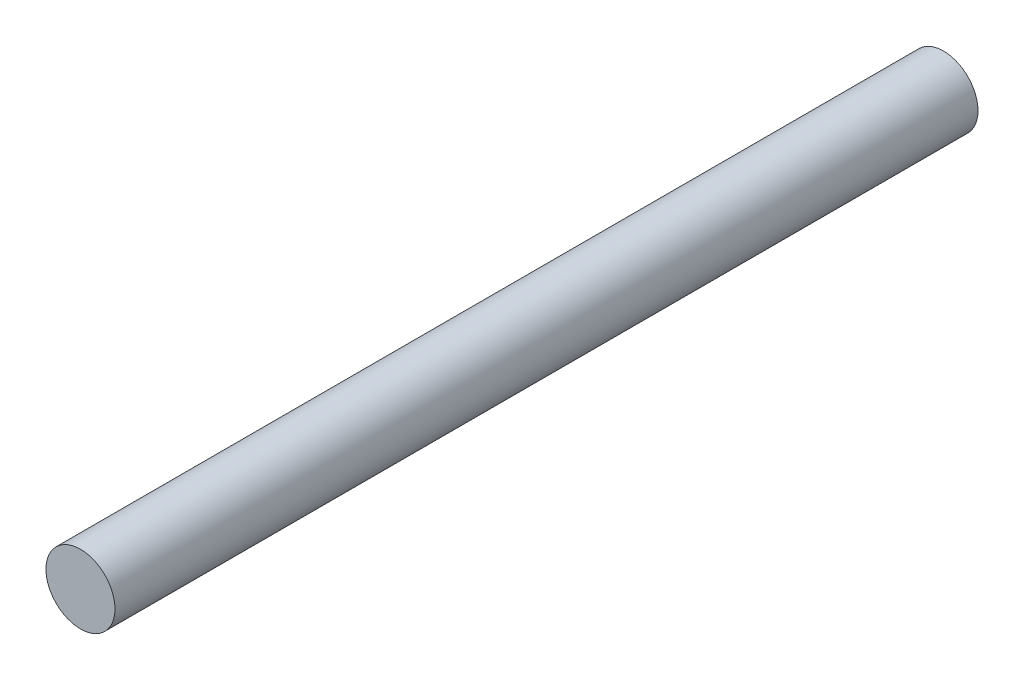
SolidWorks part; units mm, degrees
ref_plane "Alzado" through (0, 0, 0) normal (0, 0, 1) x (1, 0, 0)
ref_plane "Planta" through (0, 0, 0) normal (0, 1, 0) x (1, 0, 0)
ref_plane "Vista lateral" through (0, 0, 0) normal (1, 0, 0) x (0, 0, -1)
sketch "Croquis1" plane through (0, 0, 0) normal (0, 0, 1) x (1, 0, 0)
  circle A0 centre (0, 0) radius 4
  dimension "D1" = 8
extrude "Saliente-Extruir1" add sketch "Croquis1" along normal blind 100
